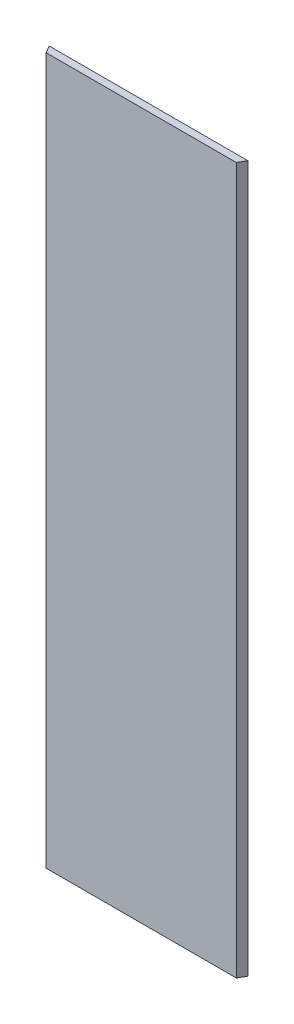
SolidWorks part; units mm, degrees
material "Maple"
ref_plane "Front Plane" through (0, 0, 0) normal (0, 0, 1) x (1, 0, 0)
ref_plane "Top Plane" through (0, 0, 0) normal (0, 1, 0) x (1, 0, 0)
ref_plane "Right Plane" through (0, 0, 0) normal (1, 0, 0) x (0, 0, -1)
sketch "Sketch1" plane through (0, 0, 0) normal (0, 0, 1) x (1, 0, 0)
  line L1 (-85.725, 304.8) -> (85.725, 304.8)
  line L2 (-85.725, 304.8) -> (-85.725, -304.8)
  line L3 (-85.725, -304.8) -> (85.725, -304.8)
  line L4 (85.725, 304.8) -> (85.725, -304.8)
  line L5 (-85.725, 304.8) -> (85.725, -304.8) construction
  line L6 (-85.725, -304.8) -> (85.725, 304.8) construction
  point P0 (0, 0)
  dimension "D1" = 171.45
  dimension "D2" = 609.6
extrude "Boss-Extrude1" add sketch "Sketch1" along normal blind 6.35
sketch "Sketch3" plane through (0, 304.8, 0) normal (0, 1, 0) x (1, 0, 0)
  line L0 (-85.725, 0) -> (-85.725, -6.35)
  line L1 (-85.725, -6.35) -> (-82.0588, -6.35)
  line L2 (85.725, -6.35) -> (-85.725, -6.35) construction
  line L3 (-82.0588, -6.35) -> (-85.725, 0)
  line L4 (82.0588, -6.35) -> (85.725, 0)
  line L5 (85.725, -6.35) -> (82.0588, -6.35)
  line L6 (85.725, 0) -> (85.725, -6.35)
  line L7 (0, -1000) -> (0, 49000) construction
  dimension "D1" = 30
extrude "Cut-Extrude1" cut sketch "Sketch3" against normal through all
